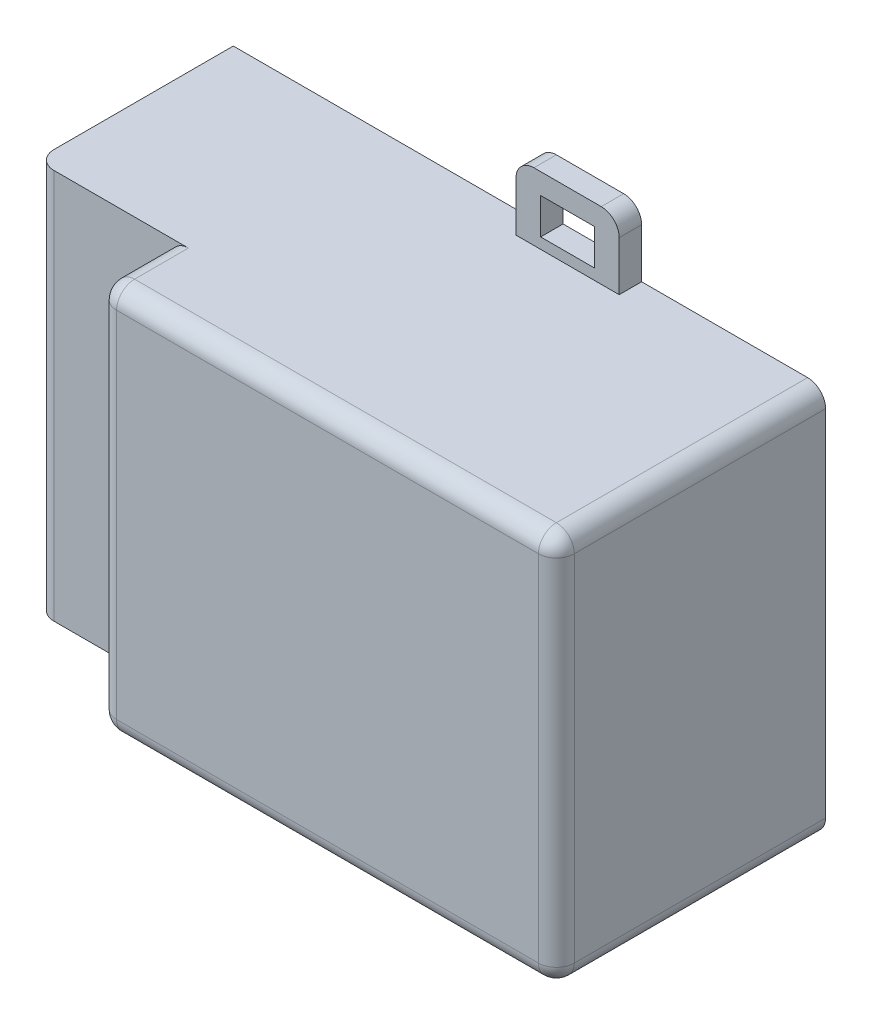
SolidWorks part; units mm, degrees
ref_plane "Plan de face" through (0, 0, 0) normal (0, 0, 1) x (1, 0, 0)
ref_plane "Plan de dessus" through (0, 0, 0) normal (0, 1, 0) x (1, 0, 0)
ref_plane "Plan de droite" through (0, 0, 0) normal (1, 0, 0) x (0, 0, -1)
sketch "Esquisse1" plane through (0, 0, 0) normal (0, 0, 1) x (1, 0, 0)
  line L0 (-30.1544, 0) -> (35.8456, 0) construction
  line L1 (-30.1544, 21.75) -> (35.8456, 21.75)
  line L2 (-30.1544, 21.75) -> (-30.1544, -21.75)
  line L3 (-30.1544, -21.75) -> (35.8456, -21.75)
  line L4 (35.8456, 21.75) -> (35.8456, -21.75)
  dimension "D1" = 66
  dimension "D2" = 43.5
extrude "Boss.-Extru.1" add sketch "Esquisse1" along normal blind 22
sketch "Esquisse2" plane through (0, 0, 22) normal (0, 0, 1) x (1, 0, 0)
  line L0 (-30.1544, -21.75) -> (35.8456, -21.75) construction
  line L1 (35.8456, 21.75) -> (-15.1544, 21.75)
  line L2 (35.8456, 21.75) -> (35.8456, -21.75)
  line L3 (35.8456, -21.75) -> (-15.1544, -21.75)
  line L4 (-15.1544, 21.75) -> (-15.1544, -21.75)
  line L5 (-30.1544, 21.75) -> (-30.1544, -21.75) construction
  dimension "D1" = 15
extrude "Boss.-Extru.2" add sketch "Esquisse2" along direction (0, 0, 1) on the side of the normal offset from surface (8 mm away) 30
sketch "Esquisse3" plane through (0, 0, 0) normal (0, 0, -1) x (-1, 0, 0)
  line L0 (-35.8456, 21.75) -> (30.1544, 21.75) construction
  line L1 (-15.3456, 21.75) -> (-3.8456, 21.75)
  line L2 (-15.3456, 21.75) -> (-15.3456, 29.25)
  line L3 (-15.3456, 29.25) -> (-3.8456, 29.25)
  line L4 (-3.8456, 21.75) -> (-3.8456, 29.25)
  line L5 (-35.8456, -21.75) -> (-35.8456, 21.75) construction
  line L6 (30.1544, 21.75) -> (30.1544, -21.75) construction
  line L7 (-9.5956, 29.25) -> (-9.5956, 21.75) construction
  line L8 (-12.5956, 26.95) -> (-6.5956, 26.95)
  line L9 (-12.5956, 26.95) -> (-12.5956, 22.95)
  line L10 (-12.5956, 22.95) -> (-6.5956, 22.95)
  line L11 (-6.5956, 26.95) -> (-6.5956, 22.95)
  line L12 (30.1544, 0) -> (-35.8456, 0) construction
  line L13 (-12.5956, -26.95) -> (-6.5956, -26.95)
  line L14 (-12.5956, -26.95) -> (-12.5956, -22.95)
  line L15 (-12.5956, -22.95) -> (-6.5956, -22.95)
  line L16 (-6.5956, -26.95) -> (-6.5956, -22.95)
  line L17 (-15.3456, -21.75) -> (-3.8456, -21.75)
  line L18 (-15.3456, -21.75) -> (-15.3456, -29.25)
  line L19 (-15.3456, -29.25) -> (-3.8456, -29.25)
  line L20 (-3.8456, -21.75) -> (-3.8456, -29.25)
  point P16 (-9.5956, 26.95)
  dimension "D1" = 32
  dimension "D2" = 7.5
  dimension "D3" = 45.5
  dimension "D4" = 6
  dimension "D5" = 4
  dimension "D6" = 2.3
extrude "Boss.-Extru.3" add sketch "Esquisse3" against normal blind 2.5
fillet "Congé1" radius 2 13 edges at (15.3456, -29.25, 1.25) (3.8456, -29.25, 1.25) (35.8456, -21.75, 15) (35.8456, 0, 30) (-15.1544, 0, 30) (10.3456, 21.75, 30) (-15.1544, 21.75, 26) (-15.1544, -21.75, 26) (10.3456, -21.75, 30) (-30.1544, 0, 22) (35.8456, 21.75, 15) (3.8456, 29.25, 1.25) (15.3456, 29.25, 1.25)
